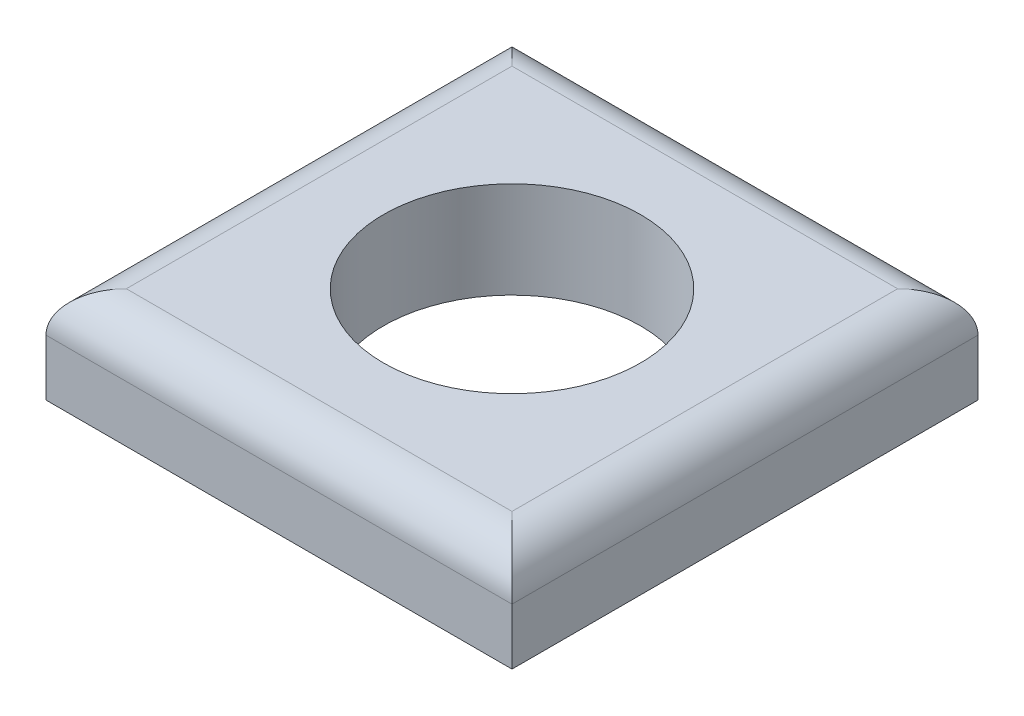
SolidWorks part; units mm, degrees
ref_plane "前视基准面" through (0, 0, 0) normal (0, 0, 1) x (1, 0, 0)
ref_plane "上视基准面" through (0, 0, 0) normal (0, 1, 0) x (1, 0, 0)
ref_plane "右视基准面" through (0, 0, 0) normal (1, 0, 0) x (0, 0, -1)
sketch "草图1" plane through (0, 0, 0) normal (0, 1, 0) x (1, 0, 0)
  line L0 (-14.6896, 0) -> (12.7218, 0) construction
  line L1 (-2.9, 2.9) -> (2.9, 2.9)
  line L2 (-2.9, 2.9) -> (-2.9, -2.9)
  line L3 (-2.9, -2.9) -> (2.9, -2.9)
  line L4 (2.9, 2.9) -> (2.9, -2.9)
  line L5 (0, 7.9866) -> (0, -8.1972) construction
  dimension "D1" = 5.8
  dimension "D2" = 5.8
extrude "拉伸1" add sketch "草图1" along normal blind 1.2
sketch "草图2" plane through (0, 1.2, 0) normal (0, 1, 0) x (-1, 0, 0)
  circle A0 centre (0, 0) radius 1.6
  dimension "D1" = 3.2
extrude "切除-拉伸1" cut sketch "草图2" against normal blind 1.2
fillet "圆角1" radius 0.5 4 edges at (0, 1.2, 2.9) (2.9, 1.2, 0) (0, 1.2, -2.9) (-2.9, 1.2, 0)
